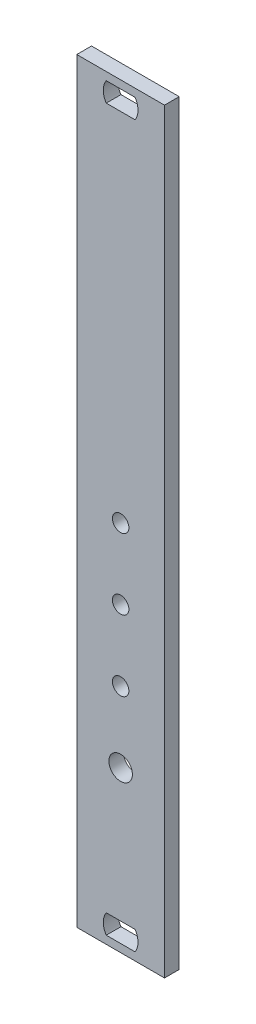
SolidWorks part; units mm, degrees
material "Alliage 1060"
ref_plane "Face" through (0, 0, 0) normal (0, 0, 1) x (1, 0, 0)
ref_plane "Dessus" through (0, 0, 0) normal (0, 1, 0) x (1, 0, 0)
ref_plane "Droite" through (0, 0, 0) normal (1, 0, 0) x (0, 0, -1)
sketch "Model" plane through (0, 0, 0) normal (0, 0, 1) x (1, 0, 0)
  line L0 (0, 128.4) -> (14.9, 128.4)
  line L1 (14.9, 0) -> (0, 0)
  line L2 (9.8954, 123.75) -> (5.0046, 123.75)
  line L3 (5.0046, 127.05) -> (9.8954, 127.05)
  line L4 (9.8954, 1.35) -> (5.0046, 1.35)
  line L5 (5.0046, 4.65) -> (9.8954, 4.65)
  line L6 (0, 0) -> (0, 128.4)
  line L7 (14.9, 128.4) -> (14.9, 0)
  line L8 (7.45, 125.4) -> (7.45, 3) construction
  line L9 (7.45, 4.65) -> (7.45, 1.35) construction
  line L10 (7.45, 127.05) -> (7.45, 123.75) construction
  arc A4 (5.0046, 4.65) -> (5.0046, 1.35) centre (7.45, 3) ccw
  arc A6 (5.0046, 127.05) -> (5.0046, 123.75) centre (7.45, 125.4) ccw
  arc A7 (9.8954, 1.35) -> (9.8954, 4.65) centre (7.45, 3) ccw
  arc A8 (9.8954, 123.75) -> (9.8954, 127.05) centre (7.45, 125.4) ccw
  point P28 (7.45, 3)
  point P31 (7.45, 125.4)
  dimension "D10" = 2.95
  dimension "D15" = 2.95
  dimension "D1" = 128.4
  dimension "D2" = 14.9
  dimension "D8" = 3
  dimension "D12" = 7.45
  dimension "D13" = 3.3
  dimension "D14" = 3
  dimension "D16" = 3.3
extrude "Boss.-Extru.1" add sketch "Model" along normal blind 2.5
sketch "Esquisse1" plane through (0, 0, 2.5) normal (0, 0, 1) x (1, 0, 0)
  line L0 (7.45, 0) -> (7.45, 128.4) construction
  line L1 (0, 0) -> (14.9, 0) construction
  line L2 (14.9, 128.4) -> (0, 128.4) construction
  circle A3 centre (7.45, 63.2) radius 1.4
  circle A4 centre (7.45, 51.2) radius 1.4
  circle A5 centre (7.45, 39.2) radius 1.4
  circle A13 centre (7.45, 27.2) radius 2
  dimension "D2" = 12
  dimension "D3" = 12
  dimension "D4" = 2.8
  dimension "D5" = 2.8
  dimension "D6" = 2.8
  dimension "D7" = 27.2
  dimension "D8" = 12
  dimension "D14" = 4
extrude "Enlèv. mat.-Extru.1" cut sketch "Esquisse1" against normal through all
